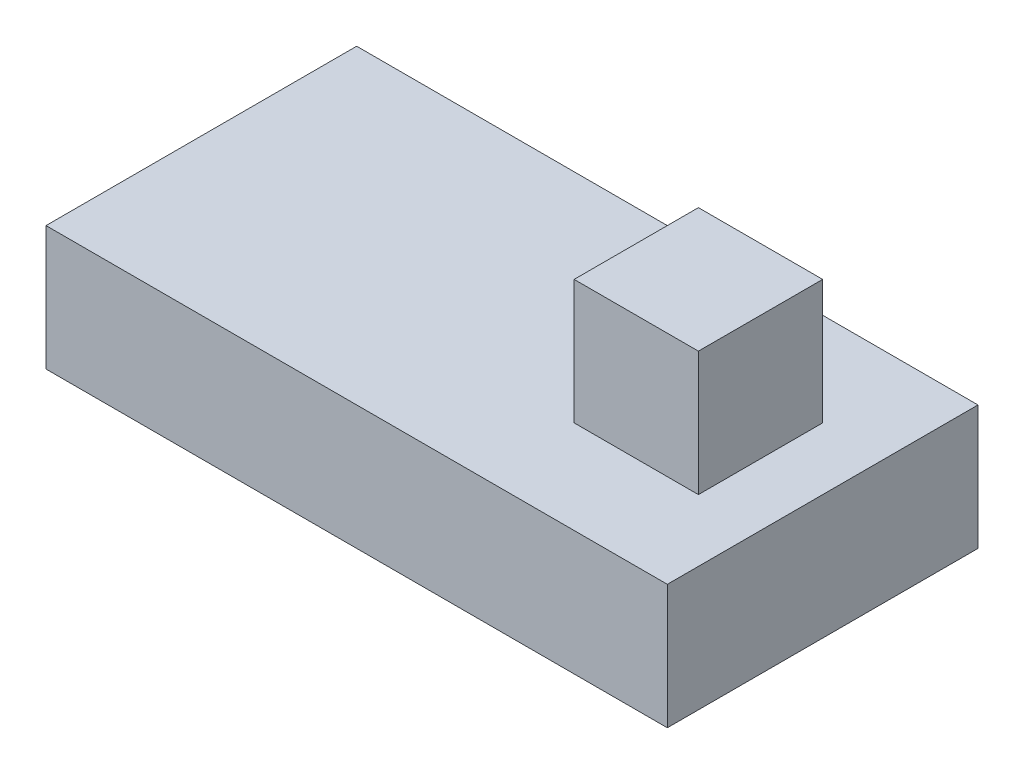
SolidWorks part; units mm, degrees
ref_plane "Спереди" through (0, 0, 0) normal (0, 0, 1) x (1, 0, 0)
ref_plane "Сверху" through (0, 0, 0) normal (0, 1, 0) x (1, 0, 0)
ref_plane "Справа" through (0, 0, 0) normal (1, 0, 0) x (0, 0, -1)
sketch "Эскиз1" plane through (0, 0, 0) normal (0, 1, 0) x (1, 0, 0)
  line L1 (0, 0) -> (200, 0)
  line L2 (0, 0) -> (0, 100)
  line L3 (0, 100) -> (200, 100)
  line L4 (200, 0) -> (200, 100)
  dimension "D1" = 100
  dimension "D2" = 200
extrude "Бобышка-Вытянуть1" add sketch "Эскиз1" along normal blind 40
sketch "Эскиз2" plane through (0, 40, 0) normal (0, 1, 0) x (1, 0, 0)
  line L0 (0, 50) -> (200, 50) construction
  line L1 (140, 30) -> (180, 30)
  line L2 (140, 30) -> (140, 70)
  line L3 (140, 70) -> (180, 70)
  line L4 (180, 30) -> (180, 70)
  line L5 (0, 100) -> (0, 0) construction
  line L6 (200, 0) -> (200, 100) construction
  line L7 (160, 100) -> (160, 0) construction
  line L8 (200, 100) -> (0, 100) construction
  line L9 (0, 0) -> (200, 0) construction
  point P16 (140, 50)
  point P17 (160, 70)
  dimension "D1" = 40
  dimension "D2" = 160
extrude "Бобышка-Вытянуть2" add sketch "Эскиз2" along normal blind 40
